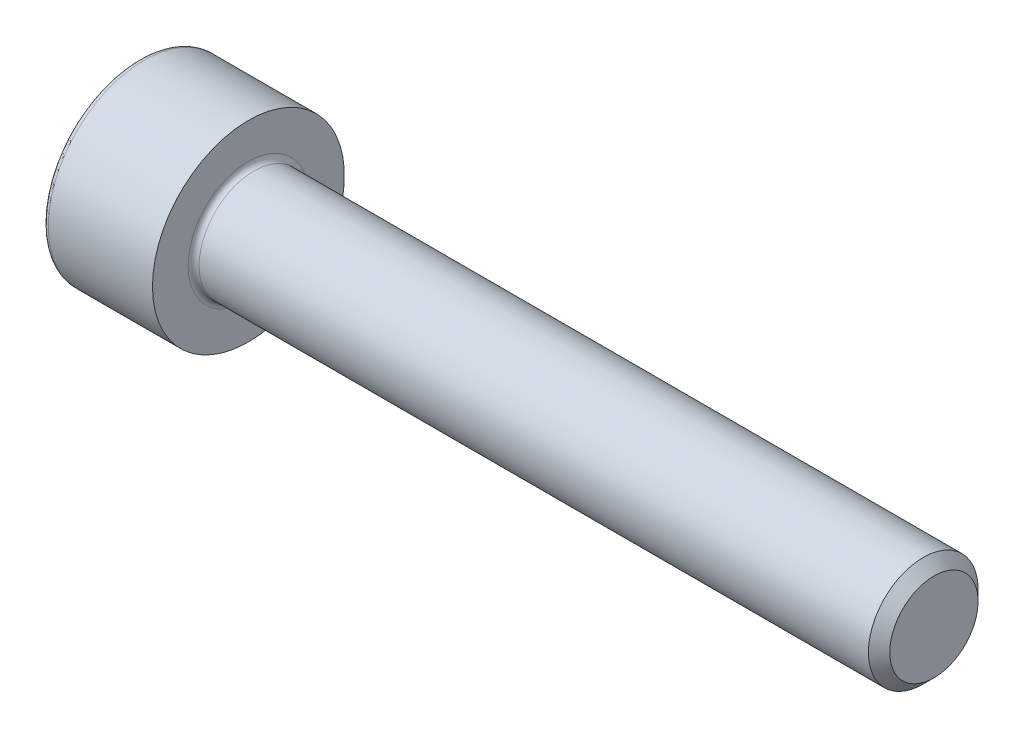
SolidWorks part; units mm, degrees
ref_plane "Front Plane" through (0, 0, 0) normal (0, 0, 1) x (1, 0, 0)
ref_plane "Top Plane" through (0, 0, 0) normal (0, 1, 0) x (1, 0, 0)
ref_plane "Right Plane" through (0, 0, 0) normal (1, 0, 0) x (0, 0, -1)
sketch "BodySke" plane through (0, 0, 0) normal (0, 0, 1) x (1, 0, 0)
  line L0 (0, 0) -> (5.8492, 0) construction
  line L1 (0, 0) -> (0, 3.5)
  line L2 (0, 3.5) -> (4, 3.5)
  line L3 (4, 3.5) -> (4, 2)
  line L4 (4, 2) -> (28.61, 2)
  line L5 (28.61, 2) -> (29, 1.61)
  line L6 (29, 1.61) -> (29, 0)
  line L7 (29, 0) -> (0, 0)
  line L8 (4, 0) -> (4, 0.601) construction
  line L9 (4.7, 1.5877) -> (4.7, 0.9267) construction
  dimension "Thread_length" = 25
  dimension "Diameter" = 4
  dimension "Thread_minor" = 3.22
  dimension "Body_chamfer_angle" = 45
  dimension "Length" = 25
  dimension "Head_diameter" = 7
  dimension "Head_length" = 4
  dimension "Advance" = 0.7
revolve "BaseBody" add sketch "BodySke" angle 360 about L0
cosmetic thread "ThreadCosmetic" [suppressed] parameters "Thread_length"=25, "Thread_minor"=3.22
fillet "Fillet1" radius 0.2 1 edges at (4, 0, 2)
fillet "Fillet2" radius 0.2 1 edges at (0, 0, 3.5)
sketch "HexSke" plane through (0, 0, 0) normal (1, 0, 0) x (0, 0, -1)
  line L1 (0, 1.7321) -> (-1.5, 0.866)
  line L2 (-1.5, 0.866) -> (-1.5, -0.866)
  line L3 (-1.5, -0.866) -> (0, -1.7321)
  line L4 (0, -1.7321) -> (1.5, -0.866)
  line L5 (1.5, -0.866) -> (1.5, 0.866)
  line L6 (1.5, 0.866) -> (0, 1.7321)
  circle A0 centre (0, 0) radius 1.5 construction
  dimension "Hex_size" = 3
extrude "Hex" cut sketch "HexSke" along normal blind 2
sketch "Hex-PreBroachSke" plane through (0, 0, 0) normal (0, 0, 1) x (1, 0, 0)
  line L0 (0, 0) -> (4.7325, 0) construction
  line L1 (0, 3.3) -> (0, -3.3) construction
  line L2 (0, 0) -> (0, 1.5)
  line L3 (0, 1.5) -> (2, 1.5)
  line L4 (2, 1.5) -> (2.866, 0)
  line L5 (2.866, 0) -> (0, 0)
  dimension "Hex_depth" = 2
  dimension "D1" = 3
  dimension "Angle" = 60
revolve "Hex-PreBroach" cut sketch "Hex-PreBroachSke" angle 360 about L0
sketch "ThdSchSke" plane through (0, 0, 0) normal (0, 0, 1) x (1, 0, 0)
  line L0 (0, 0) -> (4.4125, 0) construction
  line L1 (0, 3.3) -> (0, -3.3) construction
  line L2 (27.91, 2.4503) -> (27.91, 2)
  line L3 (27.91, 2.4503) -> (28.3603, 2.4503)
  line L4 (28.3603, 2.4503) -> (28.3603, 2)
  line L5 (28.3603, 2) -> (28.1352, 1.61)
  line L6 (28.1352, 1.61) -> (27.91, 2)
  dimension "D1" = 0.7
revolve "ThreadSchematic" [suppressed] cut sketch "ThdSchSke" angle 360 about L0
pattern_linear "ThdSchPat" [suppressed]
equation "\"Thread_length@ThreadCosmetic\" = \"Thread_length@BodySke\""
equation "\"Thread_minor@ThreadCosmetic\" = \"Thread_minor@BodySke\""
equation "\"Hex_depth@Hex-PreBroachSke\" = \"Hex_length@Hex\""
equation "\"D1@Hex-PreBroachSke\" = \"Hex_size@HexSke\""
equation "\"D1@ThdSchSke\" = \"Advance@BodySke\""
equation "\"Advance@ThdSchPat\" = \"Advance@BodySke\""
equation "\"Tooth_Num@ThdSchPat\" =  int( \"Thread_length@BodySke\" / \"Advance@BodySke\" )  - 1"
